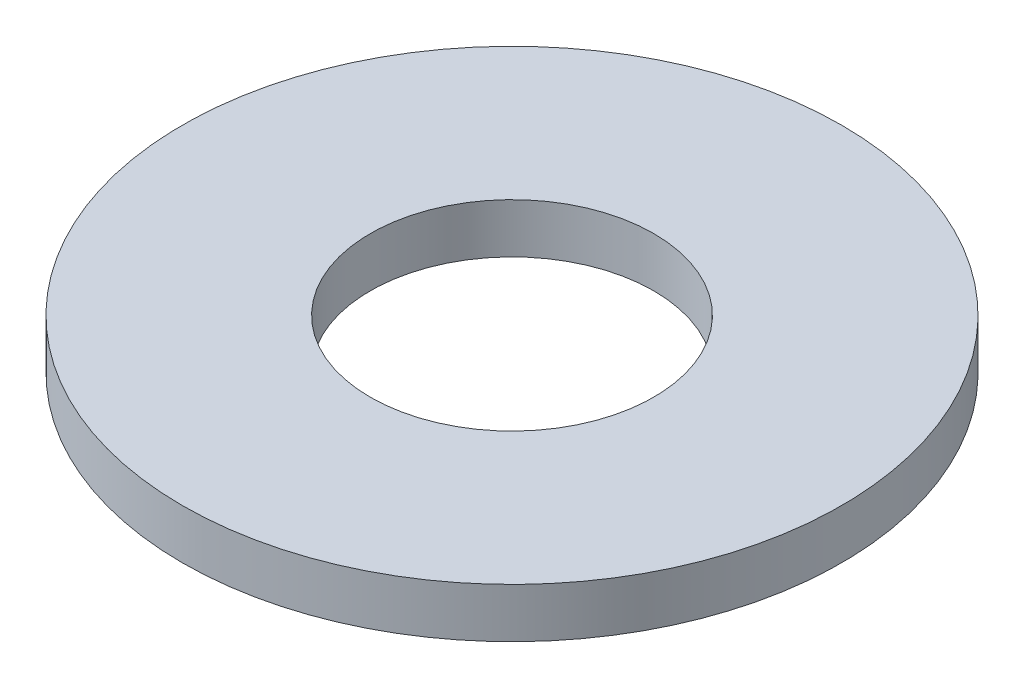
SolidWorks part; units mm, degrees
ref_plane "Front Plane" through (0, 0, 0) normal (0, 0, 1) x (1, 0, 0)
ref_plane "Top Plane" through (0, 0, 0) normal (0, 1, 0) x (1, 0, 0)
ref_plane "Right Plane" through (0, 0, 0) normal (1, 0, 0) x (0, 0, -1)
sketch "Sketch1" plane through (0, 0, 0) normal (0, 1, 0) x (1, 0, 0)
  circle A0 centre (0, 0) radius 4
  circle A1 centre (0, 0) radius 9.3
  dimension "D1" = 18.6
  dimension "D2" = 8
extrude "Boss-Extrude1" add sketch "Sketch1" along normal blind 1.4
